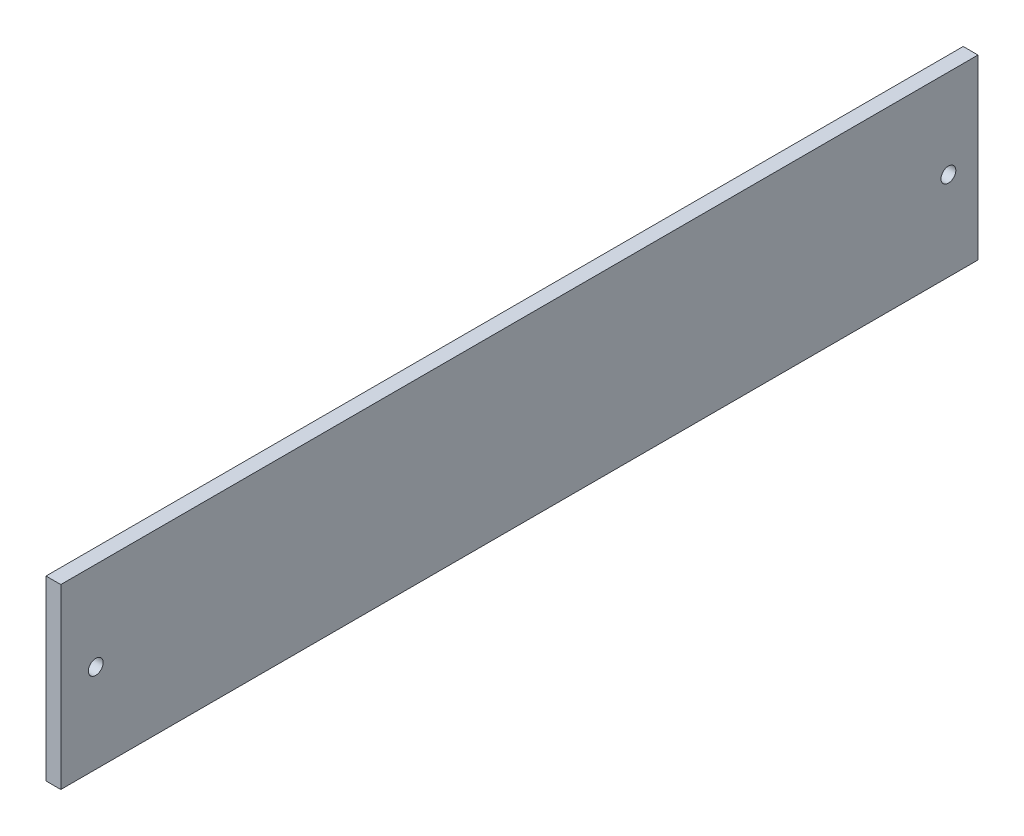
SolidWorks part; units mm, degrees
material "Plain Carbon Steel"
ref_plane "Front Plane" through (0, 0, 0) normal (0, 0, 1) x (1, 0, 0)
ref_plane "Top Plane" through (0, 0, 0) normal (0, 1, 0) x (1, 0, 0)
ref_plane "Right Plane" through (0, 0, 0) normal (1, 0, 0) x (0, 0, -1)
sketch "Sketch3" plane through (0, 0, 0) normal (1, 0, 0) x (0, 0, -1)
  line L1 (196.85, -38.1) -> (-196.85, -38.1)
  line L2 (196.85, -38.1) -> (196.85, 38.1)
  line L3 (196.85, 38.1) -> (-196.85, 38.1)
  line L4 (-196.85, -38.1) -> (-196.85, 38.1)
  line L5 (196.85, -38.1) -> (-196.85, 38.1) construction
  line L6 (196.85, 38.1) -> (-196.85, -38.1) construction
  point P0 (0, 0)
  dimension "D1" = 393.7
  dimension "D2" = 76.2
extrude "Boss-Extrude1" add sketch "Sketch3" along normal blind 6.35
sketch "Sketch4" plane through (0, 0, 0) normal (-1, 0, 0) x (0, 0, 1)
  line L1 (-196.85, 38.1) -> (196.85, 38.1) construction
  line L2 (196.85, 38.1) -> (196.85, -38.1) construction
  circle A0 centre (181.85, 0) radius 3.175
  dimension "D1" = 6.35
  dimension "D2" = 38.1
  dimension "D3" = 15
extrude "Cut-Extrude1" cut sketch "Sketch4" against normal up to surface (6.35 mm away) contours A0 up to face at (6.35, 0, 0)
sketch "Sketch6" plane through (0, 0, 0) normal (-1, 0, 0) x (0, 0, 1)
  line L0 (-196.85, -38.1) -> (-196.85, 38.1) construction
  line L1 (-196.85, 38.1) -> (196.85, 38.1) construction
  circle A0 centre (-184.15, 0) radius 3.175
  dimension "D1" = 6.35
  dimension "D2" = 12.7
  dimension "D3" = 38.1
extrude "Cut-Extrude3" cut sketch "Sketch6" against normal up to surface (6.35 mm away) up to face at (6.35, 0, 178.675)
